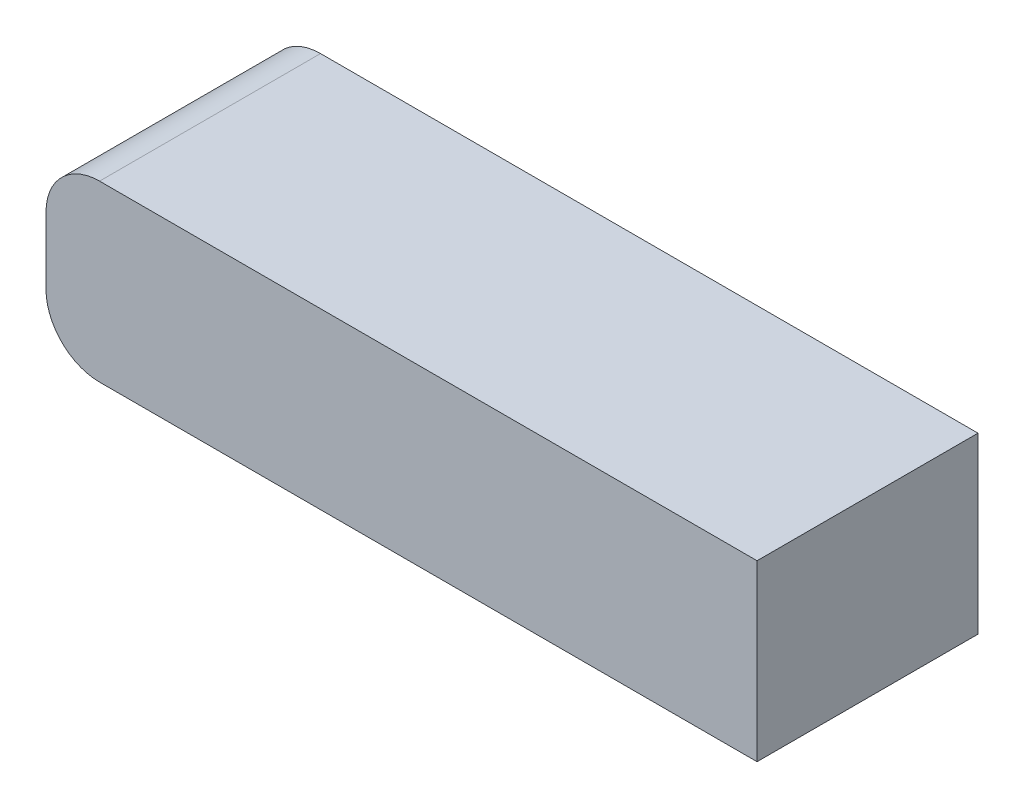
SolidWorks part; units mm, degrees
ref_plane "Front Plane" through (0, 0, 0) normal (0, 0, 1) x (1, 0, 0)
ref_plane "Top Plane" through (0, 0, 0) normal (0, 1, 0) x (1, 0, 0)
ref_plane "Right Plane" through (0, 0, 0) normal (1, 0, 0) x (0, 0, -1)
sketch "Sketch1" plane through (0, 0, 0) normal (0, 1, 0) x (1, 0, 0)
  line L1 (-67.437, -20.955) -> (67.437, -20.955)
  line L2 (-67.437, -20.955) -> (-67.437, 20.955)
  line L3 (-67.437, 20.955) -> (67.437, 20.955)
  line L4 (67.437, -20.955) -> (67.437, 20.955)
  line L5 (-67.437, -20.955) -> (67.437, 20.955) construction
  line L6 (-67.437, 20.955) -> (67.437, -20.955) construction
  point P0 (0, 0)
  dimension "D1" = 134.874
  dimension "D2" = 41.91
extrude "Boss-Extrude1" add sketch "Sketch1" along normal blind 33.02
fillet "Fillet1" radius 10.16 2 edges at (-67.437, 0, 0) (-67.437, 33.02, 0)
